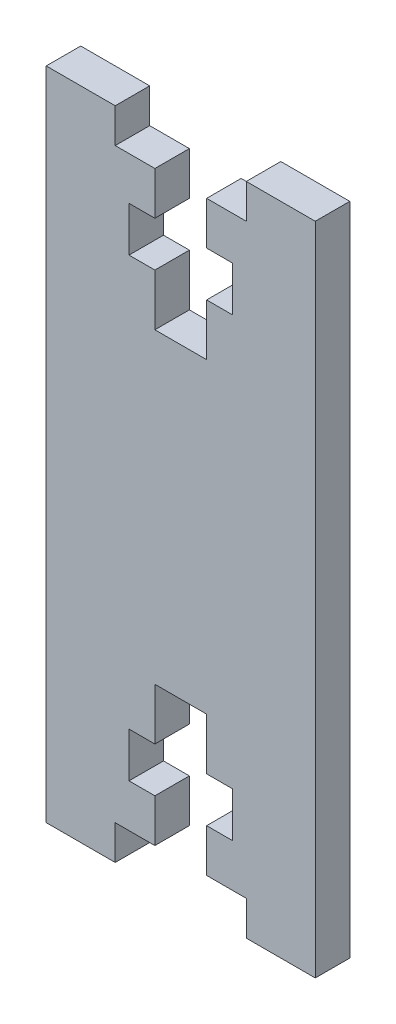
SolidWorks part; units mm, degrees
ref_plane "前视基准面" through (0, 0, 0) normal (0, 0, 1) x (1, 0, 0)
ref_plane "上视基准面" through (0, 0, 0) normal (0, 1, 0) x (1, 0, 0)
ref_plane "右视基准面" through (0, 0, 0) normal (1, 0, 0) x (0, 0, -1)
sketch "草图2" plane through (0, 0, 0) normal (0, 0, 1) x (1, 0, 0)
  line L12 (2, -29.5) -> (2, 8.5) construction
  line L18 (5.8, -27.5) -> (5.8, -29.5)
  line L19 (5.8, -29.5) -> (9.8, -29.5)
  line L20 (9.8, 8.5) -> (9.8, -29.5)
  line L21 (-1.8, -29.5) -> (-5.8, -29.5)
  line L22 (-1.8, -27.5) -> (-1.8, -29.5)
  line L23 (-5.8, -29.5) -> (-5.8, 8.5)
  line L24 (3.5, -25) -> (3.5, -27.5)
  line L25 (-1.8, -27.5) -> (0.5, -27.5)
  line L29 (2, -10.5) -> (4.7487, -10.5) construction
  line L33 (-1.8, 8.5) -> (-5.8, 8.5)
  line L34 (-1.8, 6.5) -> (0.5, 6.5)
  line L35 (3.5, 6.5) -> (5.8, 6.5)
  line L36 (5.8, 8.5) -> (9.8, 8.5)
  line L37 (-1.8, 8.5) -> (-1.8, 6.5)
  line L38 (5.8, 8.5) -> (5.8, 6.5)
  line L39 (-1, 4) -> (-1, 1.4)
  line L40 (-1, 1.4) -> (0.5, 1.4)
  line L41 (0.5, 1.4) -> (0.5, -1.6)
  line L42 (3.5, 1.4) -> (3.5, -1.6)
  line L43 (5, 1.4) -> (3.5, 1.4)
  line L44 (5, 4) -> (5, 1.4)
  line L45 (0.5, 4) -> (-1, 4)
  line L46 (0.5, -1.6) -> (3.5, -1.6)
  line L47 (3.5, 4) -> (5, 4)
  line L48 (0.5, 4) -> (0.5, 6.5)
  line L49 (3.5, 4) -> (3.5, 6.5)
  line L50 (3.5, -27.5) -> (5.8, -27.5)
  line L51 (5, -25) -> (5, -22.4)
  line L52 (5, -22.4) -> (3.5, -22.4)
  line L53 (3.5, -22.4) -> (3.5, -19.4)
  line L54 (0.5, -22.4) -> (0.5, -19.4)
  line L55 (-1, -22.4) -> (0.5, -22.4)
  line L56 (-1, -25) -> (-1, -22.4)
  line L57 (3.5, -25) -> (5, -25)
  line L58 (3.5, -19.4) -> (0.5, -19.4)
  line L59 (0.5, -25) -> (-1, -25)
  line L61 (0.5, -25) -> (0.5, -27.5)
  point P5 (2, -27.5)
extrude "凸台-拉伸1" add sketch "草图2" along normal blind 2
sketch "草图3" plane through (0, -27.5, 0) normal (0, -1, 0) x (1, 0, 0)
  line L0 (0.5, 1) -> (3.5, 1)
  line L1 (0.5, 2) -> (0.5, 0) construction
  line L2 (3.5, 2) -> (3.5, 0) construction
  circle A0 centre (2, 1) radius 1.5
sketch "草图4" plane through (0, 6.5, 0) normal (0, 1, 0) x (1, 0, 0)
  line L0 (0.5, -1) -> (3.5, -1)
  line L1 (0.5, -2) -> (0.5, 0) construction
  line L2 (3.5, -2) -> (3.5, 0) construction
  circle A0 centre (2, -1) radius 1.5
